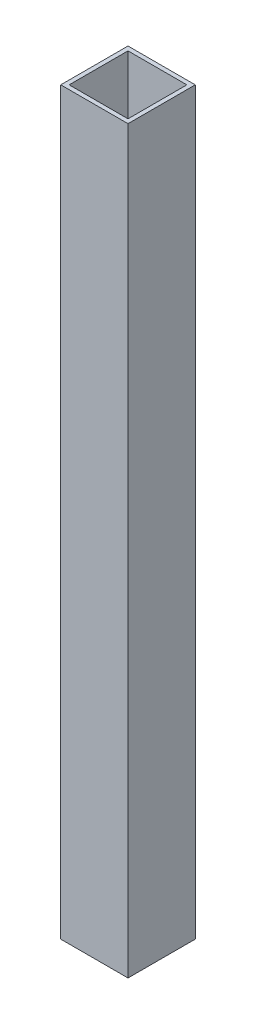
SolidWorks part; units mm, degrees
ref_plane "Front Plane" through (0, 0, 0) normal (0, 0, 1) x (1, 0, 0)
ref_plane "Top Plane" through (0, 0, 0) normal (0, 1, 0) x (1, 0, 0)
ref_plane "Right Plane" through (0, 0, 0) normal (1, 0, 0) x (0, 0, -1)
sketch "Sketch1" plane through (0, 0, 0) normal (0, 1, 0) x (1, 0, 0)
  line L1 (12.7, 12.7) -> (-12.7, 12.7)
  line L2 (12.7, 12.7) -> (12.7, -12.7)
  line L3 (12.7, -12.7) -> (-12.7, -12.7)
  line L4 (-12.7, 12.7) -> (-12.7, -12.7)
  line L5 (12.7, 12.7) -> (-12.7, -12.7) construction
  line L6 (12.7, -12.7) -> (-12.7, 12.7) construction
  line L7 (11.1125, 11.1125) -> (-11.1125, 11.1125)
  line L8 (11.1125, 11.1125) -> (11.1125, -11.1125)
  line L9 (11.1125, -11.1125) -> (-11.1125, -11.1125)
  line L10 (-11.1125, 11.1125) -> (-11.1125, -11.1125)
  line L11 (11.1125, 11.1125) -> (-11.1125, -11.1125) construction
  line L12 (11.1125, -11.1125) -> (-11.1125, 11.1125) construction
  point P0 (0, 0)
  point P6 (0, 0)
  dimension "D1" = 25.4
  dimension "D2" = 25.4
  dimension "D3" = 1.5875
  dimension "D4" = 1.5875
extrude "Boss-Extrude1" add sketch "Sketch1" along normal blind 279.4
